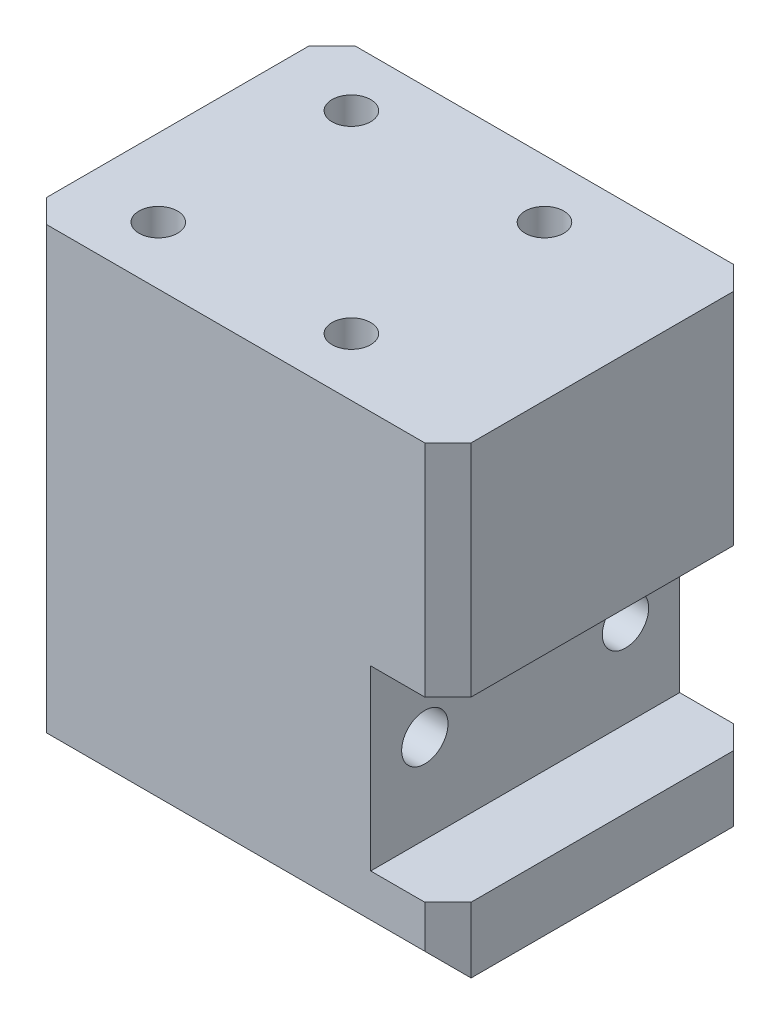
SolidWorks part; units mm, degrees
ref_plane "Front" through (0, 0, 0) normal (0, 0, 1) x (1, 0, 0)
ref_plane "Top" through (0, 0, 0) normal (0, 1, 0) x (1, 0, 0)
ref_plane "Right" through (0, 0, 0) normal (1, 0, 0) x (0, 0, -1)
sketch "草图1" plane through (0, 0, 0) normal (0, 1, 0) x (1, 0, 0)
  line L1 (11.25, -10) -> (-11.25, -10)
  line L2 (11.25, -10) -> (11.25, 10)
  line L3 (11.25, 10) -> (-11.25, 10)
  line L4 (-11.25, -10) -> (-11.25, 10)
  line L5 (11.25, -10) -> (-11.25, 10) construction
  line L6 (11.25, 10) -> (-11.25, -10) construction
  point P0 (0, 0)
  dimension "D1" = 22.5
  dimension "D2" = 20
extrude "凸台-拉伸1" add sketch "草图1" along normal blind 20
sketch "草图2" plane through (11.25, 0, 0) normal (1, 0, 0) x (0, 0, -1)
  line L0 (-10, 20) -> (10, 20) construction
  line L1 (10, 15.75) -> (-10, 15.75)
  line L2 (10, 15.75) -> (10, 20)
  line L3 (10, 20) -> (-10, 20)
  line L4 (-10, 15.75) -> (-10, 20)
  line L5 (10, 15.75) -> (-10, 20) construction
  line L6 (10, 20) -> (-10, 15.75) construction
  line L7 (-10, 20) -> (-10, 0) construction
  line L8 (10, 20) -> (10, 0) construction
  line L9 (-10, 10) -> (10, 10) construction
  line L10 (10, 0) -> (-10, 0)
  line L11 (-10, 4.25) -> (-10, 0)
  line L12 (10, 4.25) -> (-10, 4.25)
  line L13 (10, 4.25) -> (10, 0)
  point P0 (0, 17.875)
  dimension "D1" = 11.5
extrude "凸台-拉伸2" add sketch "草图2" along normal blind 5
sketch "草图3" plane through (11.25, 0, 0) normal (1, 0, 0) x (0, 0, -1)
  line L0 (-10, 10) -> (10, 10) construction
  line L1 (-10, 15.75) -> (-10, 4.25) construction
  line L2 (10, 15.75) -> (10, 4.25) construction
  line L3 (0, 15.75) -> (0, 4.25) construction
  line L4 (-10, 15.75) -> (10, 15.75) construction
  line L5 (10, 4.25) -> (-10, 4.25) construction
  circle A0 centre (6.496, 10) radius 1.5
  circle A1 centre (-6.496, 10) radius 1.5
  dimension "D1" = 3
  dimension "D2" = 3
extrude "切除-拉伸1" cut sketch "草图3" against normal through all
sketch "草图4" plane through (0, 20, 0) normal (0, 1, 0) x (1, 0, 0)
  line L0 (-11.25, 10) -> (-11.25, -10) construction
  line L1 (16.25, 10) -> (-11.25, 10)
  line L2 (16.25, 10) -> (16.25, -10)
  line L3 (16.25, -10) -> (-11.25, -10)
  line L4 (-11.25, 10) -> (-11.25, -10)
  line L5 (16.25, 10) -> (-11.25, -10) construction
  line L6 (16.25, -10) -> (-11.25, 10) construction
  line L7 (-11.25, -10) -> (16.25, -10) construction
  line L11 (16.25, 10) -> (16.25, -10) construction
  point P0 (2.5, 0)
extrude "凸台-拉伸3" add sketch "草图4" along normal blind 10
sketch "草图5" plane through (0, 30, 0) normal (0, 1, 0) x (1, 0, 0)
  line L0 (16.25, 0) -> (-11.25, 0) construction
  line L1 (16.25, -10) -> (16.25, 10) construction
  line L2 (-11.25, 10) -> (-11.25, -10) construction
  line L3 (2.5, 10) -> (2.5, -10) construction
  line L4 (16.25, 10) -> (-11.25, 10) construction
  line L5 (-11.25, -10) -> (16.25, -10) construction
  circle A0 centre (6.25, 6.25) radius 1.25
  circle A1 centre (6.25, -6.25) radius 1.25
  circle A2 centre (-6.25, 6.25) radius 1.25
  circle A3 centre (-6.25, -6.25) radius 1.25
  point P20 (0, 0)
  point P21 (-3.75, 6.25)
  point P22 (0, 0)
  point P23 (-2.7221, 6.25)
  point P24 (0, 0)
  point P25 (0, 0)
  dimension "D1" = 2.5
  dimension "D2" = 12.5
  dimension "D3" = 12.5
  dimension "D4" = 10
extrude "切除-拉伸2" cut sketch "草图5" against normal blind 15
chamfer "倒角1" distance 1.5 angle 45 9 edges at (16.25, 2.125, -10) (16.25, 22.875, -10) (-11.25, 15, -10) (2.5, 0, -10) (16.25, 22.875, 10) (16.25, 2.125, 10) (2.5, 0, 10) (-11.25, 15, 10) (-11.25, 0, 0)
